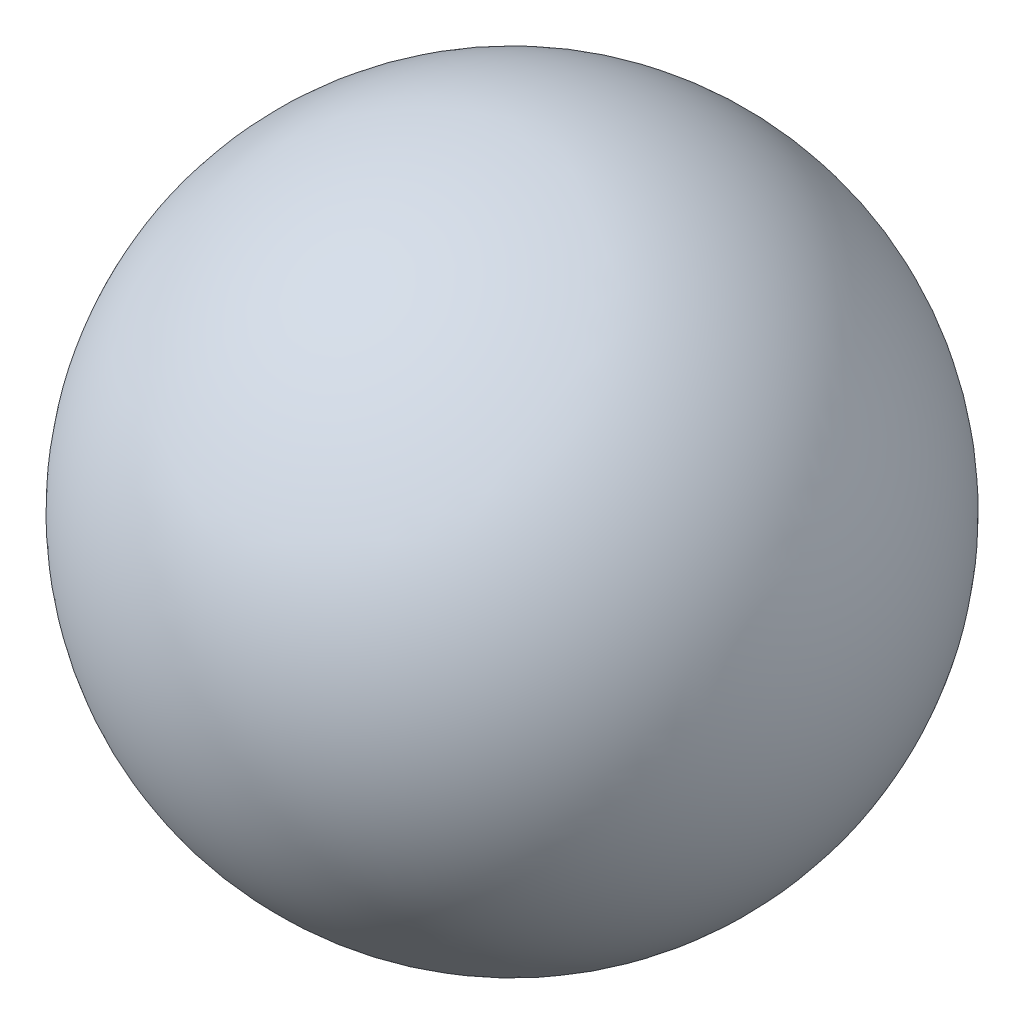
SolidWorks part; units mm, degrees
ref_plane "前视基准面" through (0, 0, 0) normal (0, 0, 1) x (1, 0, 0)
ref_plane "上视基准面" through (0, 0, 0) normal (0, 1, 0) x (1, 0, 0)
ref_plane "右视基准面" through (0, 0, 0) normal (1, 0, 0) x (0, 0, -1)
sketch "草图1" plane through (0, 0, 0) normal (0, 0, 1) x (1, 0, 0)
  line L0 (21.25, 0) -> (-21.25, 0)
  arc A0 (21.25, 0) -> (-21.25, 0) centre (0, 0) ccw
  point P6 (0, 0)
  dimension "D1" = 21.25
revolve "旋转1" add sketch "草图1" angle 360 about L0
